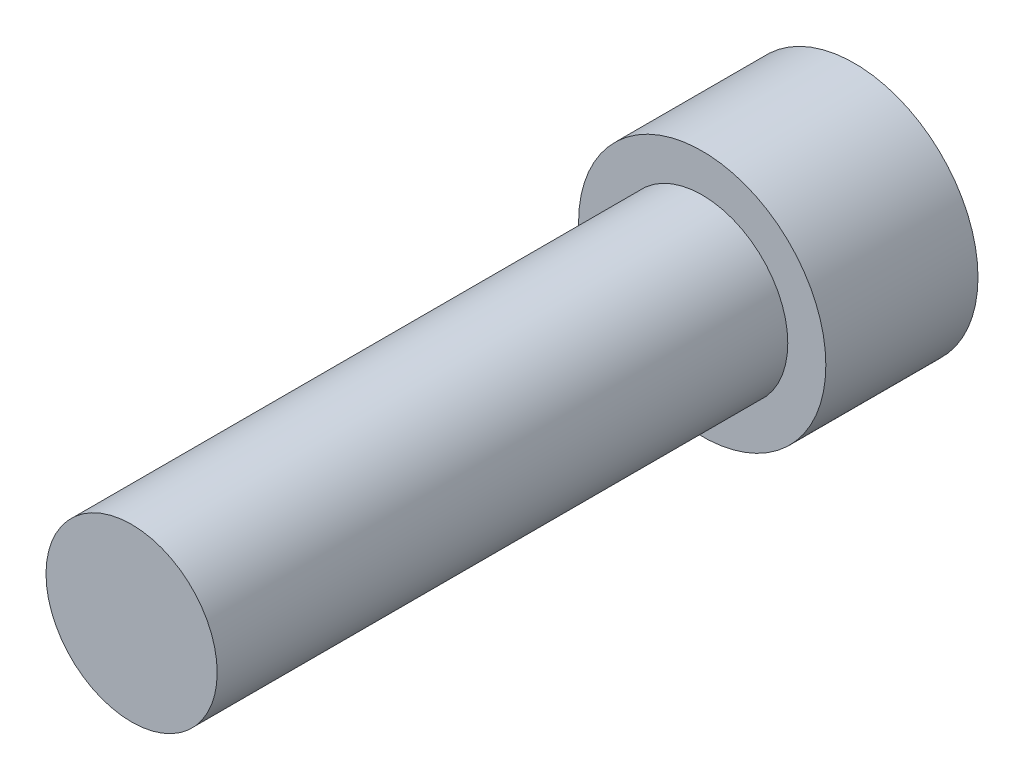
SolidWorks part; units mm, degrees
material "사용자정의 플라스틱"
ref_plane "정면" through (0, 0, 0) normal (0, 0, 1) x (1, 0, 0)
ref_plane "윗면" through (0, 0, 0) normal (0, 1, 0) x (1, 0, 0)
ref_plane "우측면" through (0, 0, 0) normal (1, 0, 0) x (0, 0, -1)
sketch "스케치1" plane through (0, 0, 0) normal (0, 0, 1) x (1, 0, 0)
  circle A0 centre (0, 0) radius 4.5
  dimension "D1" = 9
extrude "보스-돌출1" add sketch "스케치1" along normal blind 30
sketch "스케치2" plane through (0, 0, 0) normal (0, 0, -1) x (-1, 0, 0)
  circle A0 centre (0, 0) radius 6.5
  dimension "D1" = 13
extrude "보스-돌출2" add sketch "스케치2" along normal blind 8
sketch "스케치3" plane through (0, 0, -8) normal (0, 0, -1) x (-1, 0, 0)
  line L1 (1.5166, -2.2986) -> (2.7333, -0.3357)
  line L2 (2.7489, 0.1641) -> (1.6573, 2.1992)
  line L3 (1.2323, 2.4627) -> (-1.0759, 2.5349)
  line L4 (-1.5166, 2.2986) -> (-2.7333, 0.3357)
  line L5 (-2.7489, -0.1641) -> (-1.6573, -2.1992)
  line L6 (-1.2323, -2.4627) -> (1.0759, -2.5349)
  circle A0 centre (0, 0) radius 2.5 construction
  arc A1 (-1.0759, 2.5349) -> (-1.5166, 2.2986) centre (-1.0916, 2.0351) ccw
  arc A2 (1.6573, 2.1992) -> (1.2323, 2.4627) centre (1.2167, 1.9629) ccw
  arc A3 (2.7333, -0.3357) -> (2.7489, 0.1641) centre (2.3083, -0.0722) ccw
  arc A4 (1.5166, -2.2986) -> (1.0759, -2.5349) centre (1.0916, -2.0351) cw
  arc A5 (-1.6573, -2.1992) -> (-1.2323, -2.4627) centre (-1.2167, -1.9629) ccw
  arc A6 (-2.7333, 0.3357) -> (-2.7489, -0.1641) centre (-2.3083, 0.0722) ccw
  dimension "D2" = 0.5
  dimension "D1" = 5
extrude "컷-돌출1" cut sketch "스케치3" against normal blind 4
